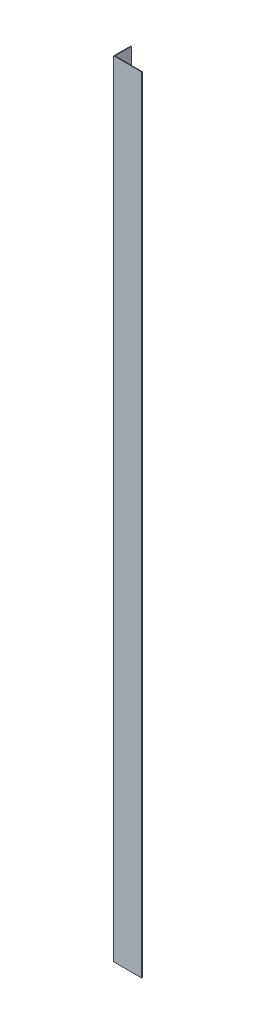
SolidWorks part; units mm, degrees
ref_plane "Front Plane" through (0, 0, 0) normal (0, 0, 1) x (1, 0, 0)
ref_plane "Top Plane" through (0, 0, 0) normal (0, 1, 0) x (1, 0, 0)
ref_plane "Right Plane" through (0, 0, 0) normal (1, 0, 0) x (0, 0, -1)
other "Configuration Table"
sketch "Sketch1" plane through (0, 0, 0) normal (0, 1, 0) x (1, 0, 0)
  line L0 (1400, -40) -> (1400, -38.5)
  line L1 (1400, -38.5) -> (1335.5, -38.5)
  line L2 (1335.5, -38.5) -> (1335.5, 0)
  line L3 (1335.5, 0) -> (1334, 0)
  line L4 (1334, 0) -> (1334, -40)
  line L5 (1334, -40) -> (1400, -40)
extrude "STORE_sove_sag_1" add sketch "Sketch1" along normal blind 1850 from offset 120 separate body
